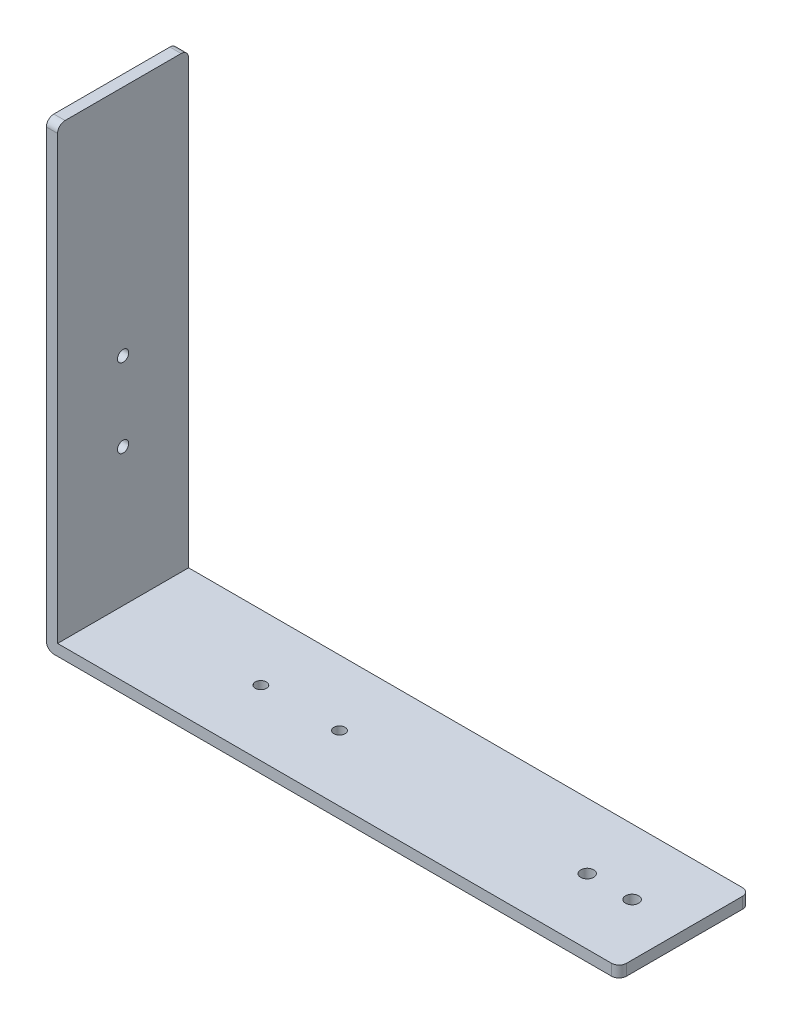
SolidWorks part; units mm, degrees
ref_plane "Plan de face" through (0, 0, 0) normal (0, 0, 1) x (1, 0, 0)
ref_plane "Plan de dessus" through (0, 0, 0) normal (0, 1, 0) x (1, 0, 0)
ref_plane "Plan de droite" through (0, 0, 0) normal (1, 0, 0) x (0, 0, -1)
sketch "Esquisse1" plane through (0, 0, 0) normal (0, 0, 1) x (1, 0, 0)
  line L0 (0, 0) -> (150, 0)
  line L1 (0, 0) -> (0, 120)
  dimension "D1" = 150
  dimension "D2" = 120
extrude "Extru.-Mince1" add sketch "Esquisse1" along normal blind 35 thin
sketch "Esquisse2" plane through (0, 0, 0) normal (0, 1, 0) x (1, 0, 0)
  line L0 (57.8827, -17.5) -> (111.6634, -17.5) construction
  line L1 (130, -3.6624) -> (130, -42.1861) construction
  line L2 (150, -35) -> (150, 0) construction
  line L3 (0, 0) -> (150, 0) construction
  circle A0 centre (124, -17.5) radius 1.75
  circle A1 centre (136, -17.5) radius 1.75
  dimension "D8" = 3.5
  dimension "D10" = 3.5
  dimension "D1" = 20
  dimension "D2" = 17.5
  dimension "D3" = 6
  dimension "D4" = 6
extrude "Enlèv. mat.-Extru.1" cut sketch "Esquisse2" against normal blind 10
fillet "Congé1" radius 2 5 edges at (150, -1.5, 35) (150, -1.5, 0) (-1.5, 120, 35) (-1.5, 120, 0) (-3, -3, 17.5)
sketch "Esquisse3" plane through (0, 0, 0) normal (0, 1, 0) x (1, 0, 0)
  line L0 (0, 0) -> (148, 0) construction
  line L1 (0, -33) -> (0, -2) construction
  circle A0 centre (36.8, -17.5) radius 1.5
  circle A1 centre (57.8, -17.5) radius 1.5
  dimension "D1" = 3
  dimension "D2" = 3
  dimension "D3" = 17.5
  dimension "D4" = 17.5
  dimension "D5" = 36.8
  dimension "D6" = 21
extrude "Enlèv. mat.-Extru.2" cut sketch "Esquisse3" against normal blind 10
sketch "Esquisse4" plane through (0, 0, 0) normal (1, 0, 0) x (0, 0, -1)
  line L0 (0, 118) -> (0, 0) construction
  line L1 (-35, 0) -> (0, 0) construction
  circle A0 centre (-17.5, 36.8) radius 1.5
  circle A1 centre (-17.5, 57.8) radius 1.5
  dimension "D5" = 3
  dimension "D6" = 3
  dimension "D1" = 17.5
  dimension "D2" = 17.5
  dimension "D3" = 36.8
  dimension "D4" = 21
extrude "Enlèv. mat.-Extru.3" cut sketch "Esquisse4" against normal blind 10
